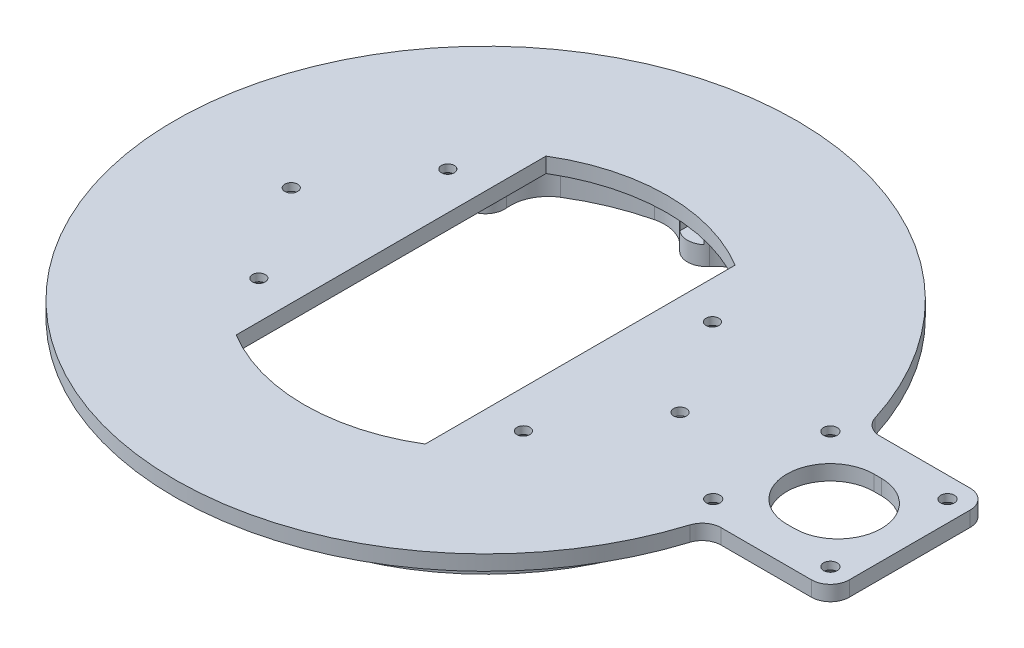
SolidWorks part; units mm, degrees
ref_plane "Plano frontal" through (0, 0, 0) normal (0, 0, 1) x (1, 0, 0)
ref_plane "Plano superior" through (0, 0, 0) normal (0, 1, 0) x (1, 0, 0)
ref_plane "Plano direito" through (0, 0, 0) normal (1, 0, 0) x (0, 0, -1)
sketch "Esboço1" plane through (0, 0, 0) normal (0, 1, 0) x (1, 0, 0)
  circle A0 centre (0, 0) radius 63.4
  circle A1 centre (0, 0) radius 60.4
  dimension "D1" = 3
  dimension "D2" = 126.8
extrude "Ressalto-extrusão1" add sketch "Esboço1" against normal blind 14
sketch "Esboço2" plane through (0, 0, 0) normal (0, 1, 0) x (1, 0, 0)
  circle A0 centre (0, 0) radius 66
  circle A1 centre (0, 0) radius 63.4
  circle A2 centre (0, 0) radius 63.4 construction
  dimension "D1" = 132
extrude "Ressalto-extrusão2" add sketch "Esboço2" against normal blind 5.2
sketch "Esboço3" plane through (0, -14, 0) normal (0, -1, 0) x (1, 0, 0)
  line L0 (-53.4, 0) -> (-63.4, 0) construction
  circle A0 centre (0, 0) radius 53.4 construction
  circle A1 centre (0, 0) radius 63.4 construction
  circle A2 centre (-58.4, 0) radius 1.6
  arc A3 (-60.2202, -4.6569) -> (-60.2202, 4.6569) centre (-58.4, 0) ccw
  arc A4 (-60.2202, 4.6569) -> (-60.2202, -4.6569) centre (0, 0) ccw
  circle A5 centre (0, 0) radius 60.4 construction
  arc A6 (-45.8751, 39.2892) -> (-39.2892, 45.8751) centre (-41.295, 41.295) ccw
  circle A7 centre (-41.295, 41.295) radius 1.6
  arc A8 (-39.2892, 45.8751) -> (-45.8751, 39.2892) centre (0, 0) ccw
  arc A9 (-4.6569, 60.2202) -> (4.6569, 60.2202) centre (0, 58.4) ccw
  circle A10 centre (0, 58.4) radius 1.6
  arc A11 (4.6569, 60.2202) -> (-4.6569, 60.2202) centre (0, 0) ccw
  arc A12 (39.2892, 45.8751) -> (45.8751, 39.2892) centre (41.295, 41.295) ccw
  circle A13 centre (41.295, 41.295) radius 1.6
  arc A14 (45.8751, 39.2892) -> (39.2892, 45.8751) centre (0, 0) ccw
  arc A15 (60.2202, 4.6569) -> (60.2202, -4.6569) centre (58.4, 0) ccw
  circle A16 centre (58.4, 0) radius 1.6
  arc A17 (60.2202, -4.6569) -> (60.2202, 4.6569) centre (0, 0) ccw
  arc A18 (45.8751, -39.2892) -> (39.2892, -45.8751) centre (41.295, -41.295) ccw
  circle A19 centre (41.295, -41.295) radius 1.6
  arc A20 (39.2892, -45.8751) -> (45.8751, -39.2892) centre (0, 0) ccw
  arc A21 (4.6569, -60.2202) -> (-4.6569, -60.2202) centre (0, -58.4) ccw
  circle A22 centre (0, -58.4) radius 1.6
  arc A23 (-4.6569, -60.2202) -> (4.6569, -60.2202) centre (0, 0) ccw
  arc A24 (-39.2892, -45.8751) -> (-45.8751, -39.2892) centre (-41.295, -41.295) ccw
  circle A25 centre (-41.295, -41.295) radius 1.6
  arc A26 (-45.8751, -39.2892) -> (-39.2892, -45.8751) centre (0, 0) ccw
  point P44 (0, 0)
  dimension "D1" = 106.8
  dimension "D2" = 3.2
  dimension "D3" = 8
extrude "Ressalto-extrusão3" add sketch "Esboço3" against normal up to surface (14 mm away) up to face at (0, 0, 60.4)
fillet "Filete1" radius 10 16 edges at (-60.2202, -7, -4.6569) (-60.2202, -7, 4.6569) (-39.2892, -7, -45.8751) (-45.8751, -7, -39.2892) (4.6569, -7, -60.2202) (-4.6569, -7, -60.2202) (45.8751, -7, -39.2892) (39.2892, -7, -45.8751) (60.2202, -7, 4.6569) (60.2202, -7, -4.6569) (39.2892, -7, 45.8751) (45.8751, -7, 39.2892) (-4.6569, -7, 60.2202) (4.6569, -7, 60.2202) (-45.8751, -7, 39.2892) (-39.2892, -7, 45.8751)
sketch "Esboço4" plane through (0, 0, 0) normal (0, 1, 0) x (1, 0, 0)
  circle A0 centre (0, 0) radius 82.26
  dimension "D1" = 164.52
extrude "Ressalto-extrusão4" add sketch "Esboço4" along normal blind 4
sketch "Esboço5" plane through (0, 4, 0) normal (0, 1, 0) x (1, 0, 0)
  line L0 (-25, 40.9756) -> (-25, -40.9756)
  line L5 (25, 40.9756) -> (25, -40.9756)
  arc A0 (-25, -40.9756) -> (25, -40.9756) centre (0, 0) ccw
  arc A1 (25, 40.9756) -> (-25, 40.9756) centre (0, 0) ccw
  dimension "D1" = 96
  dimension "D2" = 50
extrude "Corte-extrusão1" cut sketch "Esboço5" against normal up to next
sketch "Esboço6" plane through (0, 4, 0) normal (0, 1, 0) x (1, 0, 0)
  line L0 (-25, 40.9756) -> (-25, -40.9756) construction
  line L1 (0, -9.9) -> (0, 9.9) construction
  line L2 (-9.9, 0) -> (9.9, 0) construction
  circle A0 centre (-35, 25) radius 1.7
  circle A1 centre (35, 25) radius 1.7
  circle A2 centre (35, -25) radius 1.7
  circle A3 centre (-35, -25) radius 1.7
  circle A4 centre (-51.43, 0) radius 1.7
  circle A5 centre (51.43, 0) radius 1.7
  dimension "D3" = 3.4
  dimension "D1" = 25
  dimension "D2" = 10
  dimension "D4" = 51.43
extrude "Corte-extrusão2" cut sketch "Esboço6" against normal up to next
sketch "Esboço7" plane through (0, 4, 0) normal (0, 1, 0) x (1, 0, 0)
  line L0 (79.5343, 21) -> (112.2, 21)
  line L1 (112.2, 21) -> (112.2, -21)
  line L2 (112.2, -21) -> (79.5343, -21)
  arc A0 (81.9731, -6.864) -> (81.9731, 6.864) centre (91.2, 0) ccw
  arc A1 (79.5343, -21) -> (81.9731, -6.864) centre (0, 0) ccw
  circle A2 centre (0, 0) radius 82.26 construction
  arc A3 (81.9731, 6.864) -> (79.5343, 21) centre (0, 0) ccw
  point P12 (112.2, 0)
  dimension "D2" = 23
  dimension "D1" = 91.2
  dimension "D3" = 42
  dimension "D4" = 21
extrude "Ressalto-extrusão5" add sketch "Esboço7" against normal blind 4
sketch "Esboço8" plane through (0, 4, 0) normal (0, 1, 0) x (1, 0, 0)
  circle A0 centre (91.2, 0) radius 11.5
  arc A1 (81.9731, -6.864) -> (81.9731, 6.864) centre (91.2, 0) ccw construction
extrude "Corte-extrusão3" cut sketch "Esboço8" against normal up to next
sketch "Esboço9" plane through (0, 4, 0) normal (0, 1, 0) x (1, 0, 0)
  line L0 (79.7, 0) -> (102.7, 0) construction
  line L2 (91.2, -11.5) -> (91.2, 11.5) construction
  circle A0 centre (75.7, 15.5) radius 1.8
  circle A1 centre (91.2, 0) radius 11.5 construction
  circle A2 centre (106.7, 15.5) radius 1.8
  circle A3 centre (106.7, -15.5) radius 1.8
  circle A4 centre (75.7, -15.5) radius 1.8
  dimension "D1" = 15.5
  dimension "D2" = 15.5
  dimension "D3" = 3.6
extrude "Corte-extrusão4" cut sketch "Esboço9" against normal up to next
fillet "Filete2" radius 5 4 edges at (112.2, 2, 21) (112.2, 2, -21) (79.5343, 2, -21) (79.5343, 2, 21)
chamfer "Chanfro1" distance 2 angle 45 4 edges at (35, 0, 26.7) (-35, 0, -23.3) (-35, 0, 26.7) (35, 0, -23.3)
sketch "Esboço10" plane through (0, 0, 0) normal (0, -1, 0) x (1, 0, 0)
  line L0 (-54.18, 1.5877) -> (-54.18, -1.5877)
  line L1 (-54.18, -1.5877) -> (-51.43, -3.1754)
  line L2 (-51.43, -3.1754) -> (-48.68, -1.5877)
  line L3 (-48.68, -1.5877) -> (-48.68, 1.5877)
  line L4 (-48.68, 1.5877) -> (-51.43, 3.1754)
  line L5 (-51.43, 3.1754) -> (-54.18, 1.5877)
  line L6 (0, -9.9) -> (0, 9.9) construction
  line L7 (51.43, 3.1754) -> (54.18, 1.5877)
  line L8 (48.68, 1.5877) -> (51.43, 3.1754)
  line L9 (48.68, -1.5877) -> (48.68, 1.5877)
  line L10 (51.43, -3.1754) -> (48.68, -1.5877)
  line L11 (54.18, -1.5877) -> (51.43, -3.1754)
  line L12 (54.18, 1.5877) -> (54.18, -1.5877)
  circle A0 centre (-51.43, 0) radius 3.1754 construction
  circle A1 centre (51.43, 0) radius 3.1754 construction
  dimension "D1" = 5.5
extrude "Corte-extrusão5" cut sketch "Esboço10" against normal blind 2 and the other way blind 2
sketch "Esboço11" plane through (0, -14, 0) normal (0, -1, 0) x (1, 0, 0)
  line L0 (-61.15, 1.5877) -> (-61.15, -1.5877)
  line L1 (-61.15, -1.5877) -> (-58.4, -3.1754)
  line L2 (-58.4, -3.1754) -> (-55.65, -1.5877) construction
  line L3 (-55.65, -1.5877) -> (-55.65, 1.5877) construction
  line L4 (-55.65, 1.5877) -> (-58.4, 3.1754) construction
  line L5 (-58.4, 3.1754) -> (-61.15, 1.5877)
  line L6 (-58.4, 3.1754) -> (-54.5378, 3.1754)
  line L7 (-58.4, -3.1754) -> (-54.5378, -3.1754)
  line L8 (-39.0497, 43.5404) -> (-36.3187, 40.8094)
  line L9 (-39.0497, 43.5404) -> (-42.1169, 44.3623)
  line L10 (-42.1169, 44.3623) -> (-44.3623, 42.1169)
  line L11 (-44.3623, 42.1169) -> (-43.5404, 39.0497)
  line L12 (-43.5404, 39.0497) -> (-40.8094, 36.3187)
  line L13 (3.1754, 58.4) -> (3.1754, 54.5378)
  line L14 (3.1754, 58.4) -> (1.5877, 61.15)
  line L15 (1.5877, 61.15) -> (-1.5877, 61.15)
  line L16 (-1.5877, 61.15) -> (-3.1754, 58.4)
  line L17 (-3.1754, 58.4) -> (-3.1754, 54.5378)
  line L18 (43.5404, 39.0497) -> (40.8094, 36.3187)
  line L19 (43.5404, 39.0497) -> (44.3623, 42.1169)
  line L20 (44.3623, 42.1169) -> (42.1169, 44.3623)
  line L21 (42.1169, 44.3623) -> (39.0497, 43.5404)
  line L22 (39.0497, 43.5404) -> (36.3187, 40.8094)
  line L23 (58.4, -3.1754) -> (54.5378, -3.1754)
  line L24 (58.4, -3.1754) -> (61.15, -1.5877)
  line L25 (61.15, -1.5877) -> (61.15, 1.5877)
  line L26 (61.15, 1.5877) -> (58.4, 3.1754)
  line L27 (58.4, 3.1754) -> (54.5378, 3.1754)
  line L28 (39.0497, -43.5404) -> (36.3187, -40.8094)
  line L29 (39.0497, -43.5404) -> (42.1169, -44.3623)
  line L30 (42.1169, -44.3623) -> (44.3623, -42.1169)
  line L31 (44.3623, -42.1169) -> (43.5404, -39.0497)
  line L32 (43.5404, -39.0497) -> (40.8094, -36.3187)
  line L33 (-3.1754, -58.4) -> (-3.1754, -54.5378)
  line L34 (-3.1754, -58.4) -> (-1.5877, -61.15)
  line L35 (-1.5877, -61.15) -> (1.5877, -61.15)
  line L36 (1.5877, -61.15) -> (3.1754, -58.4)
  line L37 (3.1754, -58.4) -> (3.1754, -54.5378)
  line L38 (-43.5404, -39.0497) -> (-40.8094, -36.3187)
  line L39 (-43.5404, -39.0497) -> (-44.3623, -42.1169)
  line L40 (-44.3623, -42.1169) -> (-42.1169, -44.3623)
  line L41 (-42.1169, -44.3623) -> (-39.0497, -43.5404)
  line L42 (-39.0497, -43.5404) -> (-36.3187, -40.8094)
  circle A0 centre (-58.4, 0) radius 3.1754 construction
  arc A1 (-55.2739, -3.9022) -> (-55.2739, 3.9022) centre (-58.4, 0) ccw construction
  arc A2 (-54.5378, -3.1754) -> (-54.5378, 3.1754) centre (-58.4, 0) ccw
  arc A3 (-40.8094, 36.3187) -> (-36.3187, 40.8094) centre (-41.295, 41.295) ccw
  arc A4 (-3.1754, 54.5378) -> (3.1754, 54.5378) centre (0, 58.4) ccw
  arc A5 (36.3187, 40.8094) -> (40.8094, 36.3187) centre (41.295, 41.295) ccw
  arc A6 (54.5378, 3.1754) -> (54.5378, -3.1754) centre (58.4, 0) ccw
  arc A7 (40.8094, -36.3187) -> (36.3187, -40.8094) centre (41.295, -41.295) ccw
  arc A8 (3.1754, -54.5378) -> (-3.1754, -54.5378) centre (0, -58.4) ccw
  arc A9 (-36.3187, -40.8094) -> (-40.8094, -36.3187) centre (-41.295, -41.295) ccw
  circle A10 centre (0, 58.4) radius 1.6 construction
  point P65 (0, 0)
  dimension "D1" = 5.5
  dimension "D2" = 8
extrude "Corte-extrusão6" cut sketch "Esboço11" against normal blind 2.8 from offset 5 offset against normal yes
sketch "Esboço12" plane through (0, 4, 0) normal (0, 1, 0) x (1, 0, 0)
  line L0 (91.2, 0) -> (93.2, 0) construction
  line L1 (91.2, 11.5) -> (93.2, 11.5)
  line L2 (91.2, -11.5) -> (93.2, -11.5)
  arc A0 (91.2, 11.5) -> (91.2, -11.5) centre (91.2, 0) ccw
  arc A1 (93.2, -11.5) -> (93.2, 11.5) centre (93.2, 0) ccw
  circle A2 centre (91.2, 0) radius 11.5 construction
  point P4 (92.2, 0)
  dimension "D1" = 2
extrude "Corte-extrusão7" cut sketch "Esboço12" against normal blind 10
chamfer "Chanfro2" distance 2 angle 45 4 edges at (75.7, 0, 17.3) (75.7, 0, -13.7) (106.7, 0, -13.7) (106.7, 0, 17.3)
sketch "Esboço13" plane through (-43.2396, 0, -43.2396) normal (0.7071, 0, 0.7071) x (0.7071, 0, -0.7071)
  line L0 (-3.1754, -6.2) -> (3.1754, -6.2)
  line L1 (3.1754, -6.2) -> (0, -5.2)
  line L2 (0, -5.2) -> (-3.1754, -6.2)
  point P4 (0, -6.2)
  dimension "D1" = 1
extrude "Corte-extrusão8" cut sketch "Esboço13" along normal blind 10
pattern_circular "PadrãoCircular1" count 8 every 45 about axis through (0, 0, 0) along (0, 1, 0) of "Corte-extrusão8"
